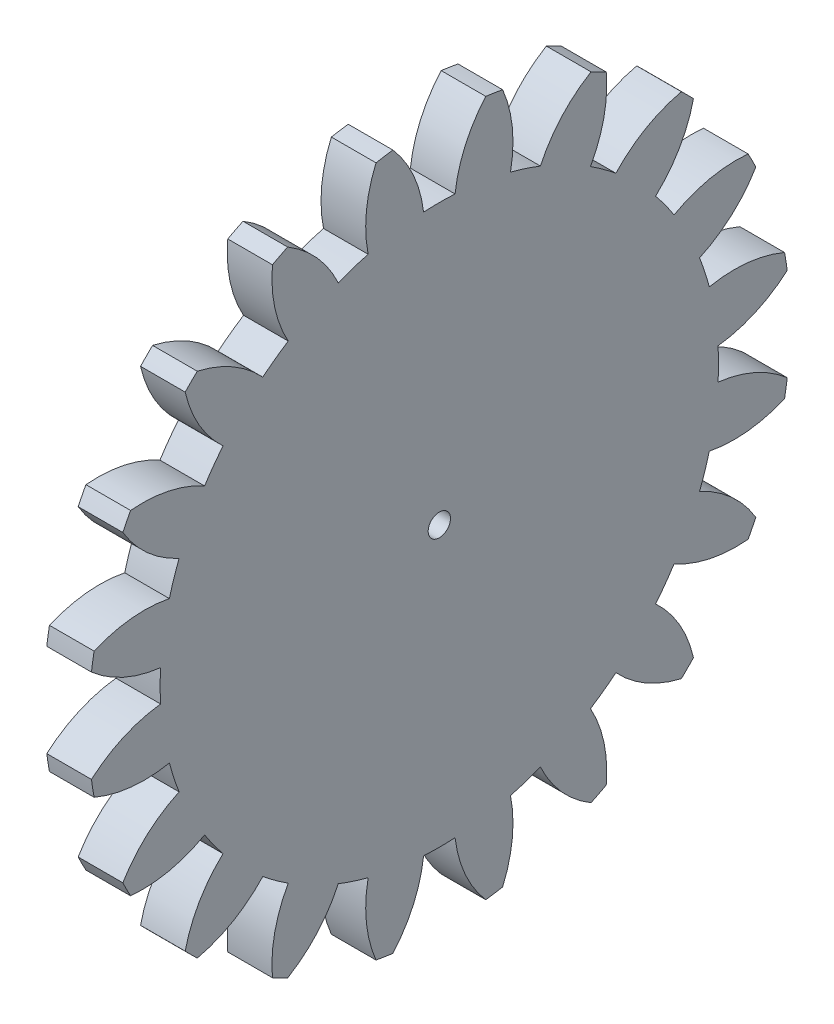
SolidWorks part; units mm, degrees
ref_plane "Plane1" through (0, 0, 0) normal (0, 0, 1) x (1, 0, 0)
ref_plane "Plane2" through (0, 0, 0) normal (0, 1, 0) x (1, 0, 0)
ref_plane "Plane3" through (0, 0, 0) normal (1, 0, 0) x (0, 0, -1)
sketch "HoldingSke" plane through (0, 0, 0) normal (0, 1, 0) x (1, 0, 0)
  line L0 (0, 0) -> (0.1879, -0.0684)
  line L1 (-15, 0) -> (100, 0) construction
  line L2 (0, 0) -> (-2.1039, 2.3779)
  line L3 (0, 0) -> (-11.863, 4.5341)
  line L4 (0, 0) -> (8.1152, 2.9537)
  line L5 (0, 0) -> (-37.4781, -13.9782)
  line L6 (0, 0) -> (-24.8689, -16.7791)
  line L7 (-2.1039, 2.3779) -> (6.5061, 41.4403)
  line L8 (-76.2, 54.61) -> (-74.4, 54.61)
  line L9 (-71.009, 38.7566) -> (-53.1078, 45.2721)
  line L10 (-76.2, 71.12) -> (104.1128, 71.12)
  line L11 (0, 0) -> (-30, 0)
  line L12 (-76.2, 101.6) -> (-76.033, 101.6)
  line L13 (24.9733, 27.94) -> (52.9518, 28.4284)
  line L14 (24.9733, 27.94) -> (24.9743, 27.94)
  line L15 (24.9733, 27.94) -> (100.4006, 29.5858)
  line L16 (-63.627, -5) -> (-12.827, -5)
  circle A0 centre (0, 0) radius 5
  circle A1 centre (0, 0) radius 12.5
  circle A2 centre (0, 0) radius 12.5
  circle A3 centre (0, 0) radius 5
  dimension "MHD" = 25
  dimension "Hub_dia" = 25
  dimension "Bore" = 10
  dimension "MBD" = 10
  dimension "Num_teeth" = 20
  dimension "Pitch" = 0.2
  dimension "Overall_len" = 40
  dimension "Show_teeth" = 20
  dimension "Thickness" = 30
  dimension "OAL" = 40.0001
  dimension "T_dim" = 1.8
  dimension "Ap" = 20
  dimension "H" = 19.05
  dimension "Pitch_radius" = 180.3128
  dimension "Width" = 30
  dimension "Backlash" = 0.167
  dimension "Addendum_fac" = 1
  dimension "Dedendum_fac" = 1.25
  dimension "Clearance_fac" = 0.25
  dimension "Dedendum_add" = 0.001
  dimension "Module" = 5
sketch "BasProSke" plane through (0, 0, 0) normal (0, 1, 0) x (1, 0, 0)
  line L0 (-10, 0) -> (60, 0) construction
  line L1 (0, 0) -> (0, 55)
  line L2 (0, 0) -> (30, 0)
  line L3 (30, 0) -> (30, 55)
  line L4 (30, 55) -> (0, 55)
  dimension "Thickness" = 30
  dimension "Diameter" = 110
revolve "Base-Revolve" add sketch "BasProSke" angle 360 about L0
sketch "TooCutSke" plane through (0, 0, 0) normal (1, 0, 0) x (0, 0, -1)
  line L1 (0, 0) -> (0, 107) construction
  line L2 (0, 0) -> (-4.2151, 49.822) construction
  line L3 (0, 0) -> (-15.6021, 98.5081) construction
  line L4 (-4.2151, 49.822) -> (-7.8011, 49.254) construction
  arc A0 (2.4648, 43.6795) -> (-2.4648, 43.6795) centre (0, 0) ccw
  arc A1 (7.3009, 54.5389) -> (-7.3009, 54.5389) centre (0, 0) ccw
  circle A2 centre (0, 0) radius 50 construction
  circle A3 centre (0, 0) radius 46.9846 construction
  arc A4 (-2.4648, 43.6795) -> (-7.3009, 54.5389) centre (-22.3276, 41.3405) ccw
  arc A5 (7.3009, 54.5389) -> (2.4648, 43.6795) centre (22.3276, 41.3405) ccw
  dimension "Root_dia" = 87.498
  dimension "Overcut_dia" = 110.0508
  dimension "Pitch_dia" = 100
  dimension "Base_dia" = 93.9693
  dimension "Flank_rad" = 20
  dimension "Half_ang" = 9
  dimension "Half_CT" = 3.6307
extrude "ToothCut" cut sketch "TooCutSke" along normal through all
fillet "Breaks" [suppressed] radius 0.1
fillet "RootFillets" [suppressed] radius 1.251
pattern_circular "TeethCuts" count 20 every 18 about axis through (-10, 0, 0) along (1, 0, 0) of "ToothCut", "RootFillets", "Breaks"
sketch "HubNeaOneSke" plane through (0, 0, 0) normal (-1, 0, 0) x (0, 0, 1)
  circle A0 centre (0, 0) radius 12.5
  dimension "Diameter" = 25
extrude "HubNearOne" [suppressed] add sketch "HubNeaOneSke" along normal blind 10.0001
sketch "HubNeaBotSke" plane through (0, 0, 0) normal (-1, 0, 0) x (0, 0, 1)
  circle A0 centre (0, 0) radius 12.5
  dimension "Diameter" = 25
extrude "HubNearBoth" add sketch "HubNeaBotSke" along normal blind 5
ref_plane "FarPln" through (30, 0, 0) normal (1, 0, 0) x (0, 0, -1)
sketch "HubFarSke" plane through (30, 0, 0) normal (1, 0, 0) x (0, 0, -1)
  circle A0 centre (0, 0) radius 12.5
  dimension "Diameter" = 25
extrude "HubFar" add sketch "HubFarSke" along normal blind 5
sketch "BorSke" plane through (0, 0, 0) normal (1, 0, 0) x (0, 0, -1)
  circle A0 centre (0, 0) radius 5
  dimension "Diameter" = 10
extrude "Bore" cut sketch "BorSke" along normal mid plane 80.0001
sketch "KeySke" plane through (0, 0, 0) normal (1, 0, 0) x (0, 0, -1)
  line L0 (-2, 0) -> (-2, 6.8)
  line L1 (-2, 6.8) -> (2, 6.8)
  line L2 (2, 6.8) -> (2, 0)
  line L3 (0, 0) -> (0, 34) construction
  line L4 (-2, 0) -> (2, 0)
  dimension "Offset" = 6.8
  dimension "Width" = 4
extrude "Keyway" [suppressed] cut sketch "KeySke" along normal mid plane 80.0001
pattern_circular "Keyway2" [suppressed] count 2 every 90 about axis through (-10, 0, 0) along (1, 0, 0)
sketch "Sketch1" plane through (-5, 0, 0) normal (-1, 0, 0) x (0, 0, 1)
  circle A0 centre (0, 0) radius 7
  circle A1 centre (0, 0) radius 1.75
  dimension "D1" = 3.5
  dimension "D2" = 14
extrude "Boss-Extrude1" add sketch "Sketch1" against normal up to surface (40.0001 mm away) up to face at (35, 0, -5)
sketch "Sketch2" plane through (35, 0, 0) normal (1, 0, 0) x (0, 0, -1)
  circle A0 centre (0, 0) radius 61.5853
extrude "Cut-Extrude1" cut sketch "Sketch2" against normal blind 28
sketch "Sketch3" plane through (-5, 0, 0) normal (-1, 0, 0) x (0, 0, 1)
  circle A0 centre (0, 0) radius 13.576
extrude "Cut-Extrude4" cut sketch "Sketch3" against normal up to surface (5 mm away) up to face at (0, 0, -12.5)
equation "' \"Module@HoldingSke\" = 6.35"
equation "' \"Num_teeth@HoldingSke\" = 12"
equation "' \"Ap@HoldingSke\" =  20"
equation "' \"Ap@HoldingSke\" = 20"
equation "' \"Width@HoldingSke\" = 0.5 * 25.4"
equation "' \"Hub_dia@HoldingSke\"= 1 * 25.4"
equation "' \"Hub_dia@HoldingSke\" = 1 * 25.4"
equation "' \"Overall_len@HoldingSke\" = 1.0 * 25.4"
equation "' \"Bore@HoldingSke\" = 0.75 * 25.4"
equation "' \"T_dim@HoldingSke\" = 0.1 * 25.4"
equation "' \"Width@KeySke\" = 0.25 * 25.4"
equation "' \"Show_teeth@HoldingSke\" = 13"
equation "' \"Backlash@HoldingSke\" = 0.009 * 25.4"
equation "' \"Addendum_fac@HoldingSke\" = 1.0"
equation "' \"Dedendum_fac@HoldingSke\" = 1.25"
equation "' \"Dedendum_add@HoldingSke\" = 0.00005 * 25.4"
equation "' \"Clearance_fac@HoldingSke\" = 0.25"
equation "\"Pitch@HoldingSke\" = 1 / \"Module@HoldingSke\""
equation "\"Overcut_dia@TooCutSke\" = (\"Num_teeth@HoldingSke\" + 2 * \"Addendum_fac@HoldingSke\") / \"Pitch@HoldingSke\" + 0.002 * 25.4"
equation "\"Pitch_dia@TooCutSke\" = \"Num_teeth@HoldingSke\" / \"Pitch@HoldingSke\""
equation "\"Base_dia@TooCutSke\" = \"Num_teeth@HoldingSke\" / \"Pitch@HoldingSke\" * cos((\"Ap@HoldingSke\"  * 3.14159265 / 180))"
equation "\"Root_dia@TooCutSke\" = (\"Num_teeth@HoldingSke\" + 2) / \"Pitch@HoldingSke\" - 2 * (\"Addendum_fac@HoldingSke\" + \"Dedendum_fac@HoldingSke\") / \"Pitch@HoldingSke\" - \"Dedendum_add@HoldingSke\" * 2"
equation "\"Half_ang@TooCutSke\" = 180 / \"Num_teeth@HoldingSke\""
equation "\"Half_CT@TooCutSke\" = \"Num_teeth@HoldingSke\" / \"Pitch@HoldingSke\" * sin((3.14159265 / 2 / \"Num_teeth@HoldingSke\")) / 2 - 7 * \"Backlash@HoldingSke\" / 4"
equation "\"Flank_rad@TooCutSke\" = \"Num_teeth@HoldingSke\" / \"Pitch@HoldingSke\" / 5"
equation "\"Radius@RootFillets\" = \"Clearance_fac@HoldingSke\" / \"Pitch@HoldingSke\" + \"Dedendum_add@HoldingSke\""
equation "\"Break_rad@Breaks\" = 0.02 / \"Pitch@HoldingSke\""
equation "\"Thickness@HoldingSke\" = \"Width@HoldingSke\""
equation "\"OAL@HoldingSke\" = \"Thickness@HoldingSke\""
equation "\"MHD@HoldingSke\" = (\"Num_teeth@HoldingSke\" + 2) / \"Pitch@HoldingSke\" - 2 * (\"Addendum_fac@HoldingSke\" + \"Dedendum_fac@HoldingSke\")  / \"Pitch@HoldingSke\" - \"Dedendum_add@HoldingSke\" * 2"
equation "\"MBD@HoldingSke\" = (\"Num_teeth@HoldingSke\" + 2) / \"Pitch@HoldingSke\" - 2 * (\"Addendum_fac@HoldingSke\" + \"Dedendum_fac@HoldingSke\")  / \"Pitch@HoldingSke\" - \"Dedendum_add@HoldingSke\" * 2 - 0.002 * 25.4"
equation "\"MHD@HoldingSke\" = ((sgn( \"MHD@HoldingSke\" - \"Hub_dia@HoldingSke\" )-1)*( \"MHD@HoldingSke\" - \"Hub_dia@HoldingSke\" ))/-2+ \"Hub_dia@HoldingSke\""
equation "\"MBD@HoldingSke\" = ((sgn( \"MBD@HoldingSke\" - \"Bore@HoldingSke\" )-1)*( \"MBD@HoldingSke\" - \"Bore@HoldingSke\" ))/-2+ \"Bore@HoldingSke\""
equation "\"OAL@HoldingSke\" = ((sgn( \"OAL@HoldingSke\" - \"Overall_len@HoldingSke\" )+1)*( \"OAL@HoldingSke\" - \"Overall_len@HoldingSke\" ))/2 + \"Overall_len@HoldingSke\" + 0.000002 * 25.4"
equation "\"Num_teeth@TeethCuts\" = int( \"Show_teeth@HoldingSke\" ) + 1"
equation "\"Num_teeth@TeethCuts\" = ((sgn( \"Num_teeth@TeethCuts\" - \"Num_teeth@HoldingSke\" )-1)*( \"Num_teeth@TeethCuts\" - \"Num_teeth@HoldingSke\" ))/-2+ \"Num_teeth@HoldingSke\""
equation "\"Num_teeth@TeethCuts\" = ((sgn( \"Num_teeth@TeethCuts\" - 2.0)+1)*( \"Num_teeth@TeethCuts\" - 2.0))/2 +2.0"
equation "\"Angle@TeethCuts\" = 360.0 / \"Num_teeth@HoldingSke\""
equation "\"Diameter@BasProSke\" = (\"Num_teeth@HoldingSke\" + 2 * \"Addendum_fac@HoldingSke\") / \"Pitch@HoldingSke\""
equation "\"Thickness@BasProSke\"  = \"Thickness@HoldingSke\""
equation "' \"Fillet_rad@BasProSke\" =  \"Thickness@HoldingSke\" * 0.05"
equation "' \"Fillet_rad@BasProSke\" = \"Thickness@HoldingSke\" * 0.05"
equation "\"MHD@HoldingSke\" = ((sgn( \"MHD@HoldingSke\" - \"Root_dia@TooCutSke\" )-1)*( \"MHD@HoldingSke\" - \"Root_dia@TooCutSke\" ))/-2+ \"Root_dia@TooCutSke\""
equation "\"Diameter@HubNeaOneSke\" = \"MHD@HoldingSke\""
equation "\"Length@HubNearOne\" = \"OAL@HoldingSke\" - \"Thickness@BasProSke\""
equation "\"Diameter@HubNeaBotSke\" = \"MHD@HoldingSke\""
equation "\"Length@HubNearBoth\" = ( \"OAL@HoldingSke\" - \"Thickness@BasProSke\" ) / 2.0"
equation "\"Thickness@FarPln\" = \"Thickness@BasProSke\""
equation "\"Diameter@HubFarSke\" = \"MHD@HoldingSke\""
equation "\"Length@HubFar\" = ( \"OAL@HoldingSke\" - \"Thickness@BasProSke\" ) / 2.0"
equation "\"Diameter@BorSke\" = \"MBD@HoldingSke\""
equation "\"D1@Bore\" = \"OAL@HoldingSke\" * 2.0"
equation "\"D1@Keyway\" = \"OAL@HoldingSke\" * 2.0"
equation "\"Offset@KeySke\" = \"T_dim@HoldingSke\" + \"MBD@HoldingSke\" / 2.0"
